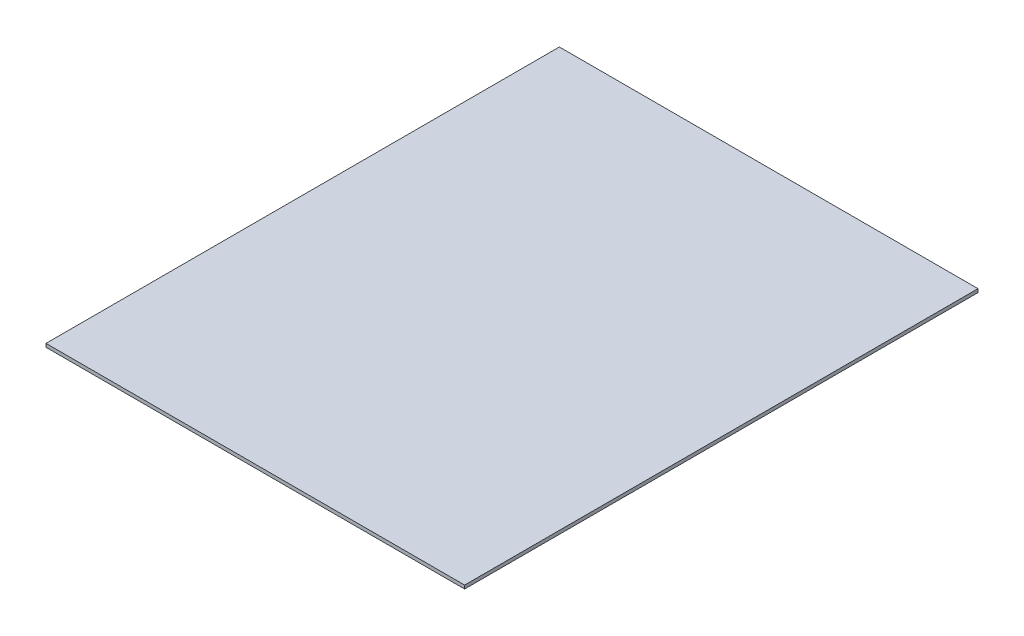
SolidWorks part; units mm, degrees
ref_plane "前视基准面" through (0, 0, 0) normal (0, 0, 1) x (1, 0, 0)
ref_plane "上视基准面" through (0, 0, 0) normal (0, 1, 0) x (1, 0, 0)
ref_plane "右视基准面" through (0, 0, 0) normal (1, 0, 0) x (0, 0, -1)
other "Configuration Table"
sketch "草图1" plane through (0, 0, 0) normal (0, 1, 0) x (1, 0, 0)
  line L1 (-3037.5, -3725) -> (3037.5, -3725)
  line L2 (-3037.5, -3725) -> (-3037.5, 3725)
  line L3 (-3037.5, 3725) -> (3037.5, 3725)
  line L4 (3037.5, -3725) -> (3037.5, 3725)
  line L5 (-3037.5, -3725) -> (3037.5, 3725) construction
  line L6 (-3037.5, 3725) -> (3037.5, -3725) construction
  point P0 (0, 0)
  dimension "D1" = 6075
  dimension "D2" = 7450
extrude "凸台-拉伸1" add sketch "草图1" along normal blind 50
